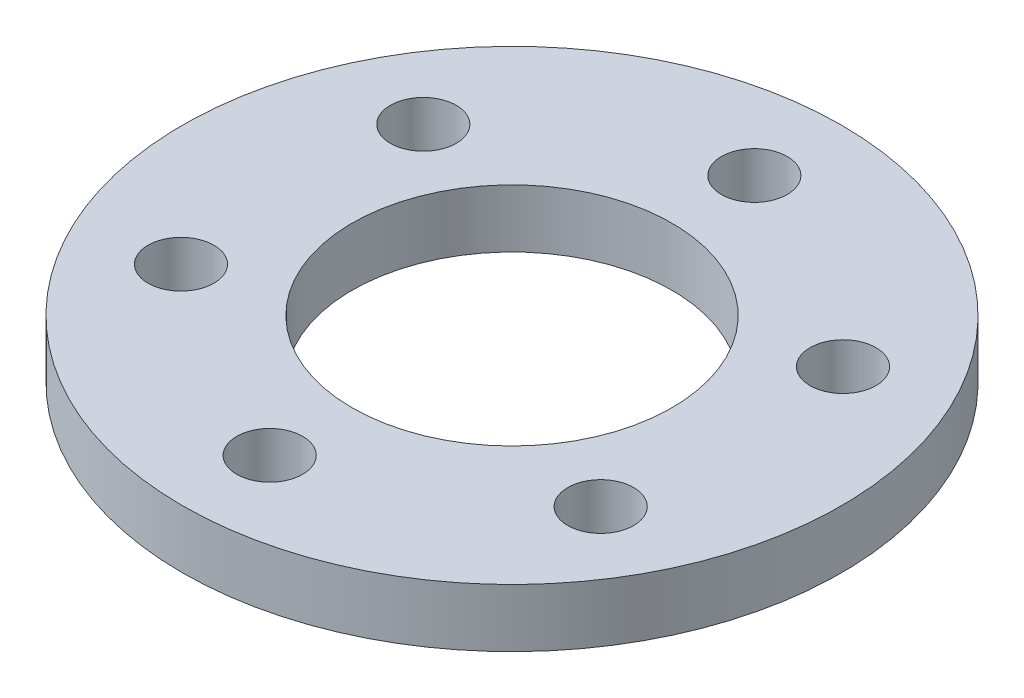
SolidWorks part; units mm, degrees
ref_plane "Front Plane" through (0, 0, 0) normal (0, 0, 1) x (1, 0, 0)
ref_plane "Top Plane" through (0, 0, 0) normal (0, 1, 0) x (1, 0, 0)
ref_plane "Right Plane" through (0, 0, 0) normal (1, 0, 0) x (0, 0, -1)
sketch "Sketch1" plane through (0, 0, 0) normal (0, 1, 0) x (1, 0, 0)
  circle A0 centre (0, 0) radius 17
  circle A1 centre (0, 0) radius 8.25
  circle A2 centre (0, 0) radius 12.5 construction
  circle A3 centre (0, 12.5) radius 1.7
  circle A6 centre (0, 0) radius 12 construction
  circle A7 centre (10.8253, 6.25) radius 1.7
  circle A8 centre (10.8253, -6.25) radius 1.7
  circle A9 centre (0, -12.5) radius 1.7
  circle A10 centre (-10.8253, -6.25) radius 1.7
  circle A11 centre (-10.8253, 6.25) radius 1.7
  point P13 (0, 0)
  point P21 (0, 0)
  dimension "D1" = 34
  dimension "D2" = 16.5
  dimension "D3" = 25
  dimension "D4" = 3.4
  dimension "D6" = 24
  dimension "D5" = 6
extrude "Boss-Extrude1" add sketch "Sketch1" along normal blind 3
